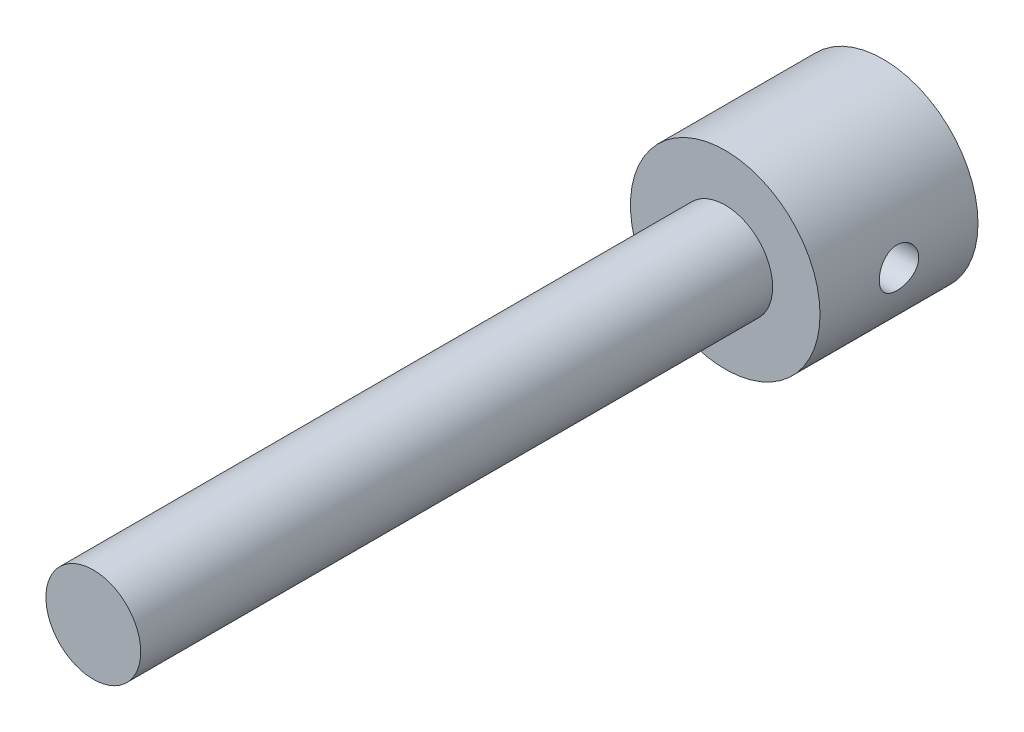
SolidWorks part; units mm, degrees
ref_plane "Ön Düzlem" through (0, 0, 0) normal (0, 0, 1) x (1, 0, 0)
ref_plane "Üst Düzlem" through (0, 0, 0) normal (0, 1, 0) x (1, 0, 0)
ref_plane "Sağ Düzlem" through (0, 0, 0) normal (1, 0, 0) x (0, 0, -1)
sketch "Çizim1" plane through (0, 0, 0) normal (0, 0, 1) x (1, 0, 0)
  circle A0 centre (0, 0) radius 12
  dimension "D1" = 24
extrude "Yükseklik-Ekstrüzyon1" add sketch "Çizim1" along normal blind 20
sketch "Çizim2" plane through (0, 0, 20) normal (0, 0, 1) x (1, 0, 0)
  circle A0 centre (0, 0) radius 6
  dimension "D1" = 12
extrude "Yükseklik-Ekstrüzyon2" add sketch "Çizim2" along normal blind 80
cosmetic thread "Kozmetik Diş Açma1" parameters "D2"=10.072
sketch "Çizim3" plane through (0, 0, 0) normal (1, 0, 0) x (0, 0, -1)
  line L0 (0, -12) -> (0, 12) construction
  line L1 (0, 12) -> (-20, 12) construction
  circle A0 centre (-10, 0) radius 2.5
  dimension "D1" = 5
  dimension "D2" = 10
  dimension "D3" = 12
extrude "Kes-Ekstrüzyon1" cut sketch "Çizim3" against normal mid plane 80
